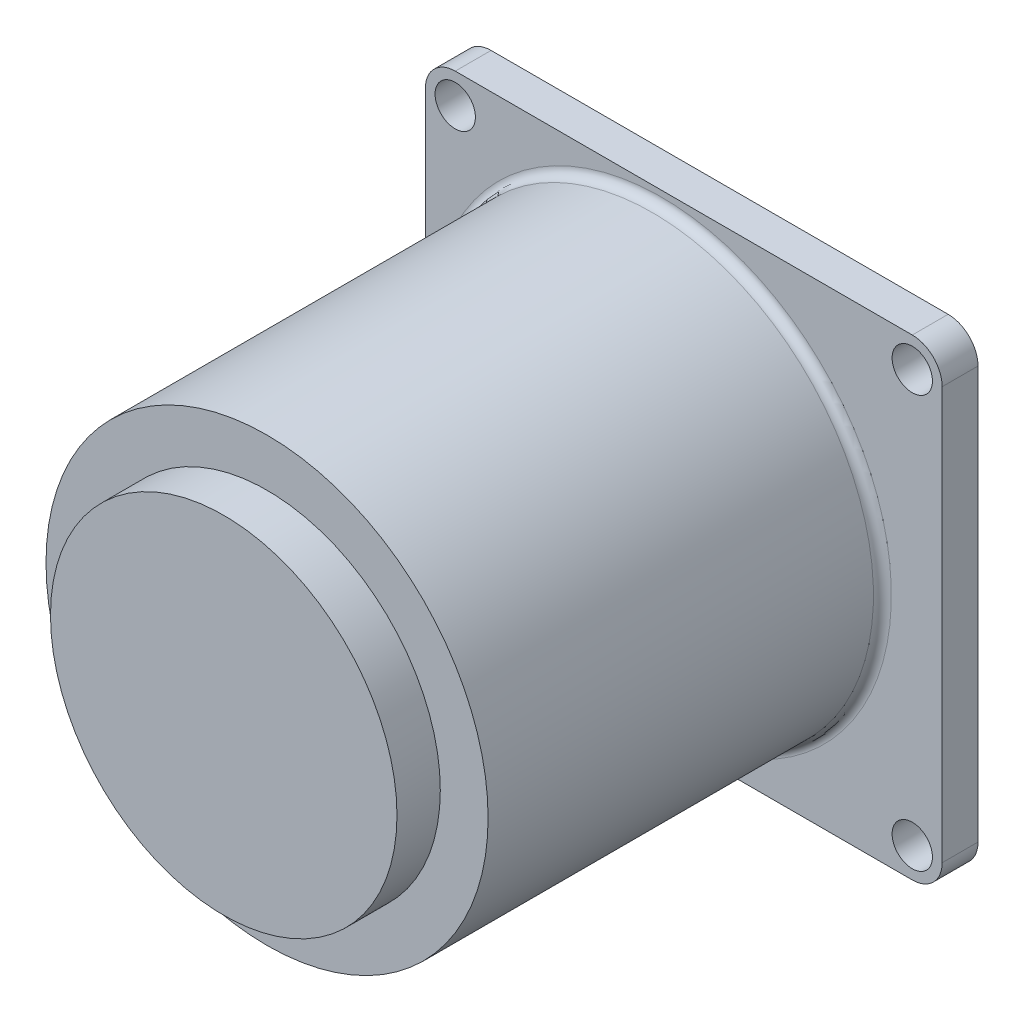
SolidWorks part; units mm, degrees
material "6061-T6 (SS)"
ref_plane "Ebene vorne" through (0, 0, 0) normal (0, 0, 1) x (1, 0, 0)
ref_plane "Ebene oben" through (0, 0, 0) normal (0, 1, 0) x (1, 0, 0)
ref_plane "Ebene rechts" through (0, 0, 0) normal (1, 0, 0) x (0, 0, -1)
sketch "Skizze1" plane through (0, 0, 0) normal (0, 0, 1) x (1, 0, 0)
  line L1 (0, 0) -> (173, 0)
  line L2 (0, 0) -> (0, 158)
  line L3 (0, 158) -> (173, 158)
  line L4 (173, 0) -> (173, 158)
  dimension "D1" = 173
  dimension "D2" = 158
extrude "Aufsatz-Linear austragen1" add sketch "Skizze1" along normal blind 12
fillet "Verrundung1" radius 10 4 edges at (0, 0, 6) (0, 158, 6) (173, 158, 6) (173, 0, 6)
sketch "Skizze2" plane through (0, 0, 12) normal (0, 0, 1) x (1, 0, 0)
  line L0 (0, 79) -> (79, 79) construction
  line L1 (0, 148) -> (0, 10) construction
  circle A0 centre (79, 79) radius 74
  dimension "D2" = 148
  dimension "D1" = 79
extrude "Aufsatz-Linear austragen2" add sketch "Skizze2" along normal blind 132
sketch "Skizze3" plane through (0, 0, 144) normal (0, 0, 1) x (1, 0, 0)
  circle A0 centre (79, 79) radius 58
  dimension "D1" = 116
extrude "Aufsatz-Linear austragen3" add sketch "Skizze3" along normal blind 14.5
sketch "Skizze4" plane through (0, 0, 0) normal (0, 0, -1) x (-1, 0, 0)
  line L0 (-86.5, 158) -> (-86.5, 0) construction
  line L1 (-163, 158) -> (-10, 158) construction
  line L2 (-10, 0) -> (-163, 0) construction
  line L3 (-173, 79) -> (0, 79) construction
  line L4 (-173, 10) -> (-173, 148) construction
  line L5 (0, 148) -> (0, 10) construction
  circle A0 centre (-163, 148) radius 6.75
  circle A1 centre (-10, 148) radius 6.75
  circle A2 centre (-10, 10) radius 6.75
  circle A3 centre (-163, 10) radius 6.75
  dimension "D1" = 13.5
extrude "Schnitt-Linear austragen1" cut sketch "Skizze4" against normal up to surface (12 mm away) up to face at (153, 79, 12)
fillet "Verrundung2" radius 3 1 edges at (153, 79, 12)
scale "Skalieren1" scale about origin uniform scaling yes scale factor 2
equation "\"74x2\"=95.5431"
